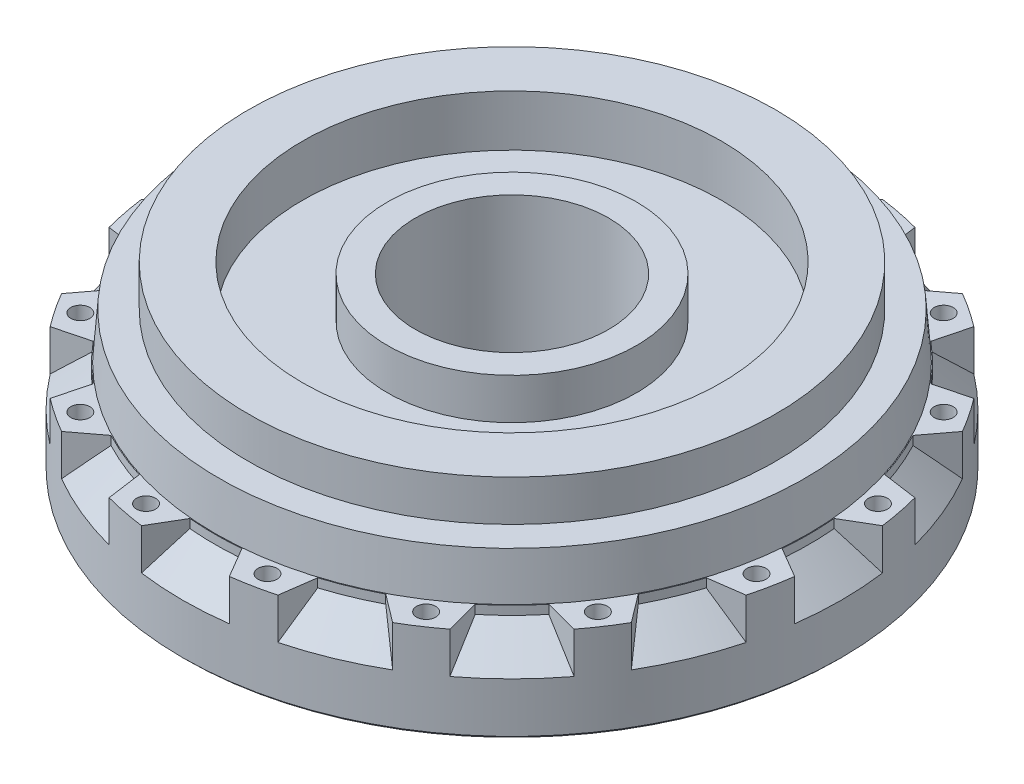
SolidWorks part; units mm, degrees
ref_plane "Front Plane" through (0, 0, 0) normal (0, 0, 1) x (1, 0, 0)
ref_plane "Top Plane" through (0, 0, 0) normal (0, 1, 0) x (1, 0, 0)
ref_plane "Right Plane" through (0, 0, 0) normal (1, 0, 0) x (0, 0, -1)
sketch "Sketch1" plane through (0, 0, 0) normal (0, 0, 1) x (1, 0, 0)
  line L0 (0, 0) -> (0, 110.1562) construction
  line L1 (225, 0) -> (225, 64)
  line L2 (225, 64) -> (202.5, 64)
  line L3 (202.5, 64) -> (200, 95.5)
  line L4 (200, 95.5) -> (180, 95.5)
  line L5 (180, 95.5) -> (180, 123.5)
  line L6 (180, 123.5) -> (143, 123.5)
  line L7 (143, 123.5) -> (143, 88.5)
  line L8 (143, 88.5) -> (85, 88.5)
  line L9 (85, 88.5) -> (85, 116.5)
  line L10 (85, 116.5) -> (66, 116.5)
  line L11 (66, 116.5) -> (66, -41.0156)
  line L12 (66, -41.0156) -> (86.5078, -41.0156)
  line L13 (86.5078, -41.0156) -> (86.5078, 0)
  line L14 (86.5078, 0) -> (225, 0)
  line L15 (225, 0) -> (0, 0) construction
  dimension "D1" = 450
  dimension "D2" = 405
  dimension "D3" = 400
  dimension "D4" = 360
  dimension "D5" = 286
  dimension "D6" = 170
  dimension "D7" = 132
  dimension "D8" = 64
  dimension "D9" = 95.5
  dimension "D10" = 123.5
  dimension "D11" = 88.5
  dimension "D12" = 116.5
revolve "Revolve1" add sketch "Sketch1" angle 360 about L0
sketch "Sketch3" plane through (0, 64, 0) normal (0, 1, 0) x (1, 0, 0)
  line L0 (0, 0) -> (225, 0) construction
  line L1 (222.991, 30) -> (201.7424, 17.5)
  line L2 (222.991, -30) -> (201.7424, -17.5)
  circle A0 centre (0, 0) radius 225 construction
  circle A1 centre (0, 0) radius 202.5 construction
  arc A2 (201.7424, -17.5) -> (201.7424, 17.5) centre (0, 0) ccw
  arc A3 (222.991, -30) -> (222.991, 30) centre (0, 0) ccw
  dimension "D1" = 60
  dimension "D2" = 35
extrude "Cut-Extrude1" cut sketch "Sketch3" against normal blind 28
pattern_circular "CirPattern1" count 16 over 360 about axis through (0, 0, 0) along (0, 1, 0) of "Cut-Extrude1"
sketch "Sketch4" plane through (0, 0, 0) normal (0, 0, 1) x (1, 0, 0)
  line L0 (225, 36) -> (203, 58)
  line L2 (-225, 0) -> (225, 0) construction
  line L3 (195, 0) -> (225, 0)
  line L4 (225, 0) -> (225, 36)
  line L5 (203, 58) -> (203, 64)
  line L7 (217.4974, 64) -> (193.0826, 64) construction
  line L8 (195, 64) -> (195, 0)
  line L9 (0, 0) -> (0, 178.2439) construction
  line L10 (203, 64) -> (195, 64)
  dimension "D1" = 22
  dimension "D2" = 45
  dimension "D3" = 30
revolve "Revolve2" add sketch "Sketch4" angle 360 about L9
sketch "Sketch5" plane through (0, 64, 0) normal (0, 1, 0) x (1, 0, 0)
  line L0 (220.6767, 43.8953) -> (208.4169, 41.4567) construction
  circle A0 centre (0, 0) radius 212.5 construction
  circle A1 centre (208.4169, 41.4567) radius 6.5
  arc A2 (222.991, 30) -> (217.4974, 57.6186) centre (0, 0) ccw construction
  circle A3 centre (208.4169, -41.4567) radius 6.5
  circle A4 centre (176.6873, -118.0587) radius 6.5
  circle A5 centre (118.0587, -176.6873) radius 6.5
  circle A6 centre (41.4567, -208.4169) radius 6.5
  circle A7 centre (-41.4567, -208.4169) radius 6.5
  circle A8 centre (-118.0587, -176.6873) radius 6.5
  circle A9 centre (-176.6873, -118.0587) radius 6.5
  circle A10 centre (-208.4169, -41.4567) radius 6.5
  circle A11 centre (-208.4169, 41.4567) radius 6.5
  circle A12 centre (-176.6873, 118.0587) radius 6.5
  circle A13 centre (-118.0587, 176.6873) radius 6.5
  circle A14 centre (-41.4567, 208.4169) radius 6.5
  circle A15 centre (41.4567, 208.4169) radius 6.5
  circle A16 centre (118.0587, 176.6873) radius 6.5
  circle A17 centre (176.6873, 118.0587) radius 6.5
  point P10 (0, 0)
  point P11 (0, 0)
  point P41 (0, 0)
  dimension "D1" = 425
  dimension "D2" = 13
  dimension "D3" = 16
extrude "Cut-Extrude2" cut sketch "Sketch5" against normal through all
chamfer "Chamfer1" distance 2 angle 45 1 edges at (0, 0, -225)
